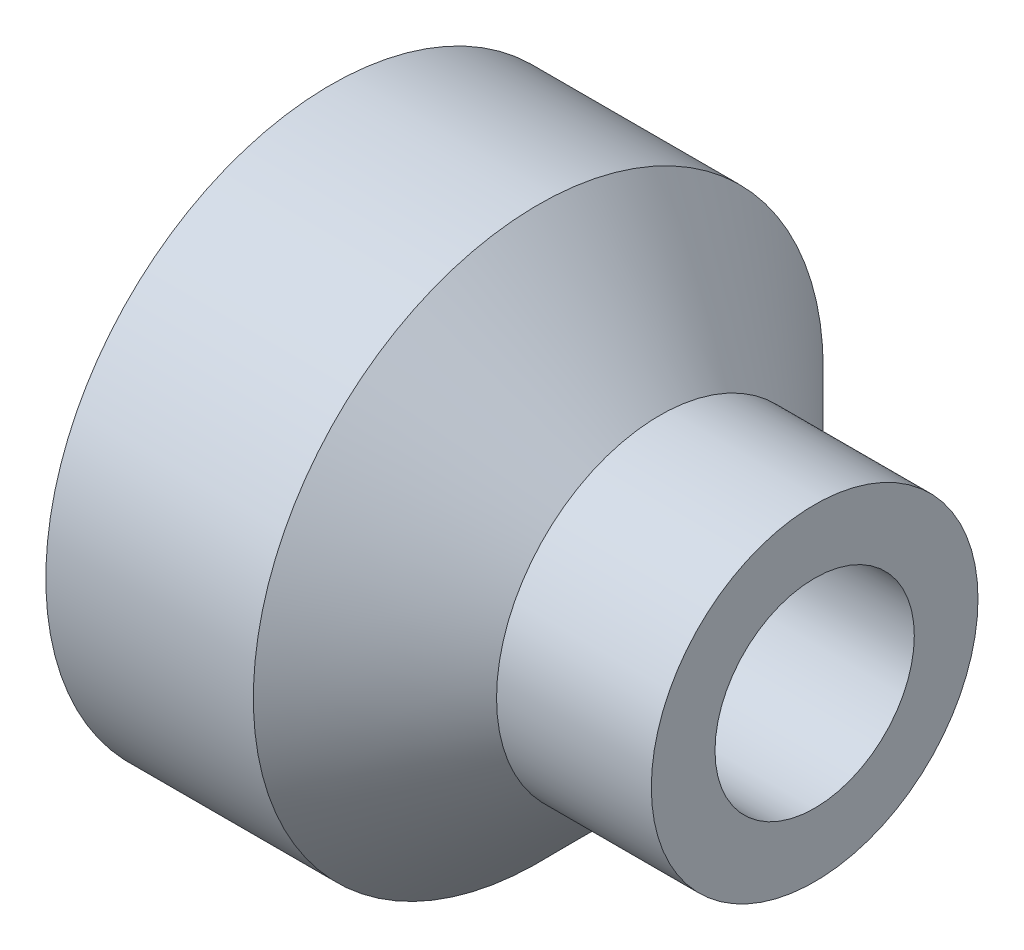
SolidWorks part; units mm, degrees
ref_plane "Front Plane" through (0, 0, 0) normal (0, 0, 1) x (1, 0, 0)
ref_plane "Top Plane" through (0, 0, 0) normal (0, 1, 0) x (1, 0, 0)
ref_plane "Right Plane" through (0, 0, 0) normal (1, 0, 0) x (0, 0, -1)
sketch "Sketch1" plane through (0, 0, 0) normal (0, 0, 1) x (1, 0, 0)
  line L0 (-3.5624, 4.546) -> (-0.2516, 4.546)
  line L1 (-0.2516, 4.546) -> (1.6884, 2.606)
  line L2 (1.6884, 2.606) -> (4.1576, 2.606)
  line L3 (4.1576, 2.606) -> (4.1576, 1.59)
  line L4 (4.1576, 1.59) -> (1.2676, 1.59)
  line L5 (1.2676, 1.59) -> (-0.6724, 3.53)
  line L6 (-0.6724, 3.53) -> (-3.5624, 3.53)
  line L7 (-3.5624, 3.53) -> (-3.5624, 4.546)
  line L8 (0, 2.8576) -> (0.7184, 3.576) construction
  line L9 (0, 0) -> (-50000, 0) construction
  dimension "D1" = 45
  dimension "D2" = 3.53
  dimension "D3" = 1.59
  dimension "D4" = 2.89
  dimension "D5" = 1.016
revolve "Revolve1" add sketch "Sketch1" angle 360 about L9
